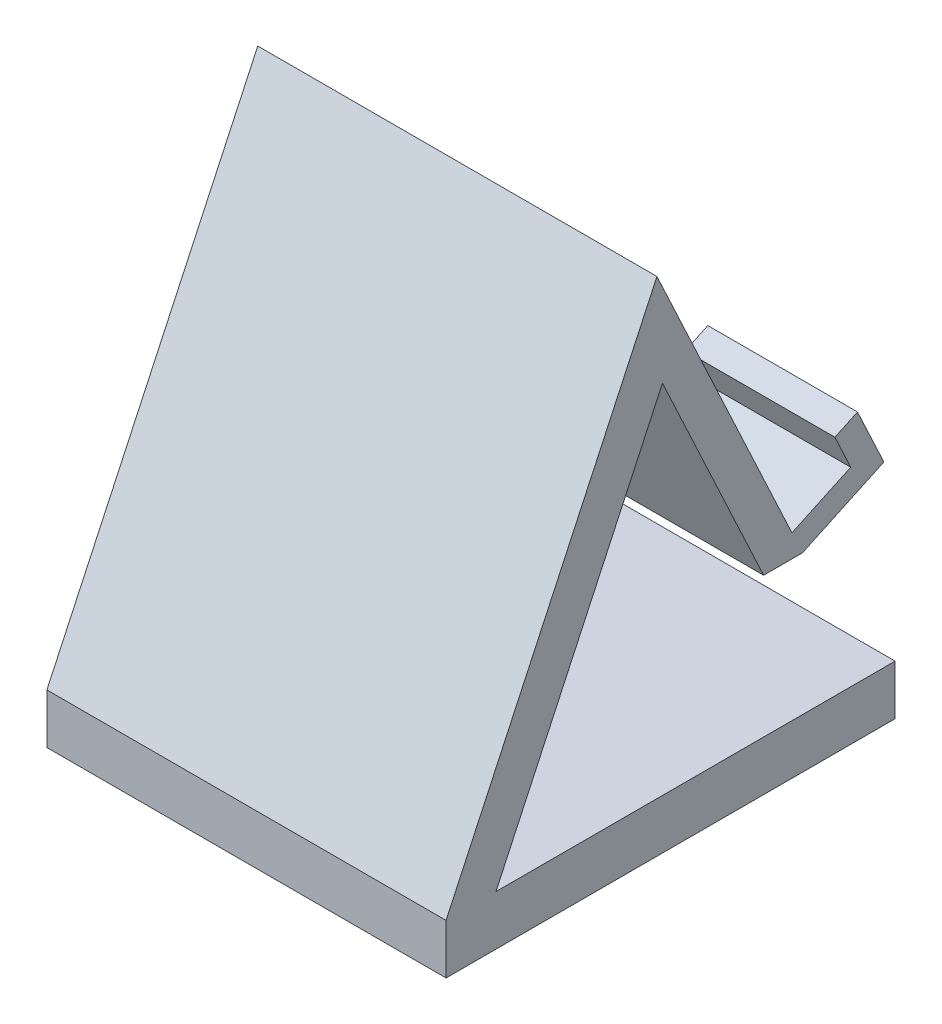
SolidWorks part; units mm, degrees
material "PLA"
ref_plane "Front Plane" through (0, 0, 0) normal (0, 0, 1) x (1, 0, 0)
ref_plane "Top Plane" through (0, 0, 0) normal (0, 1, 0) x (1, 0, 0)
ref_plane "Right Plane" through (0, 0, 0) normal (1, 0, 0) x (0, 0, -1)
other "Center of Mass"
sketch "Sketch1" plane through (0, 0, 0) normal (1, 0, 0) x (0, 0, -1)
  line L0 (0, 10) -> (42.2618, 100.6308)
  line L1 (0, 0) -> (90, 0)
  line L2 (0, 0) -> (0, 10)
  line L3 (10, 10) -> (90, 10)
  line L4 (90, 0) -> (90, 10)
  line L5 (10, 10) -> (43.3688, 81.5597)
  line L6 (42.2618, 100.6308) -> (46.0749, 92.4536)
  line L7 (46.0749, 92.4536) -> (71.432, 38.0752)
  line L8 (43.3688, 81.5597) -> (63.646, 38.0752)
  line L9 (63.646, 38.0752) -> (71.432, 38.0752)
  dimension "D1" = 90
  dimension "D2" = 65
  dimension "D3" = 100
  dimension "D4" = 65
  dimension "D5" = 10
  dimension "D6" = 10
  dimension "D7" = 90
  dimension "D8" = 60
  dimension "D9" = 50
  dimension "D10" = 50
  dimension "D11" = 50
extrude "Boss-Extrude1" add sketch "Sketch1" along normal blind 80
sketch "Sketch2" plane through (0, 34.1605, -73.2574) normal (0, 0.4226, -0.9063) x (-1, 0, 0)
  line L1 (-80, 4.3194) -> (-50, 4.3194)
  line L2 (-80, 4.3194) -> (-80, 9.3194)
  line L3 (-80, 9.3194) -> (-50, 9.3194)
  line L4 (-50, 4.3194) -> (-50, 9.3194)
  line L5 (0, 4.3194) -> (-30, 4.3194)
  line L6 (0, 4.3194) -> (0, 9.3194)
  line L7 (0, 9.3194) -> (-30, 9.3194)
  line L8 (-30, 4.3194) -> (-30, 9.3194)
  dimension "D1" = 30
  dimension "D2" = 5
  dimension "D3" = 30
  dimension "D4" = 5
extrude "Boss-Extrude2" add sketch "Sketch2" along normal blind 13
sketch "Sketch3" plane through (0, 39.6545, -85.0394) normal (0, 0.4226, -0.9063) x (-1, 0, 0)
  line L1 (-80, 4.3194) -> (-50, 4.3194)
  line L2 (-80, 4.3194) -> (-80, 16.8194)
  line L3 (-80, 16.8194) -> (-50, 16.8194)
  line L4 (-50, 4.3194) -> (-50, 16.8194)
  line L5 (-30, 4.3194) -> (0, 4.3194)
  line L6 (-30, 4.3194) -> (-30, 16.8194)
  line L7 (-30, 16.8194) -> (0, 16.8194)
  line L8 (0, 4.3194) -> (0, 16.8194)
  dimension "D1" = 12.5
  dimension "D2" = 30
  dimension "D3" = 30
  dimension "D4" = 12.5
extrude "Boss-Extrude3" add sketch "Sketch3" along normal blind 5
